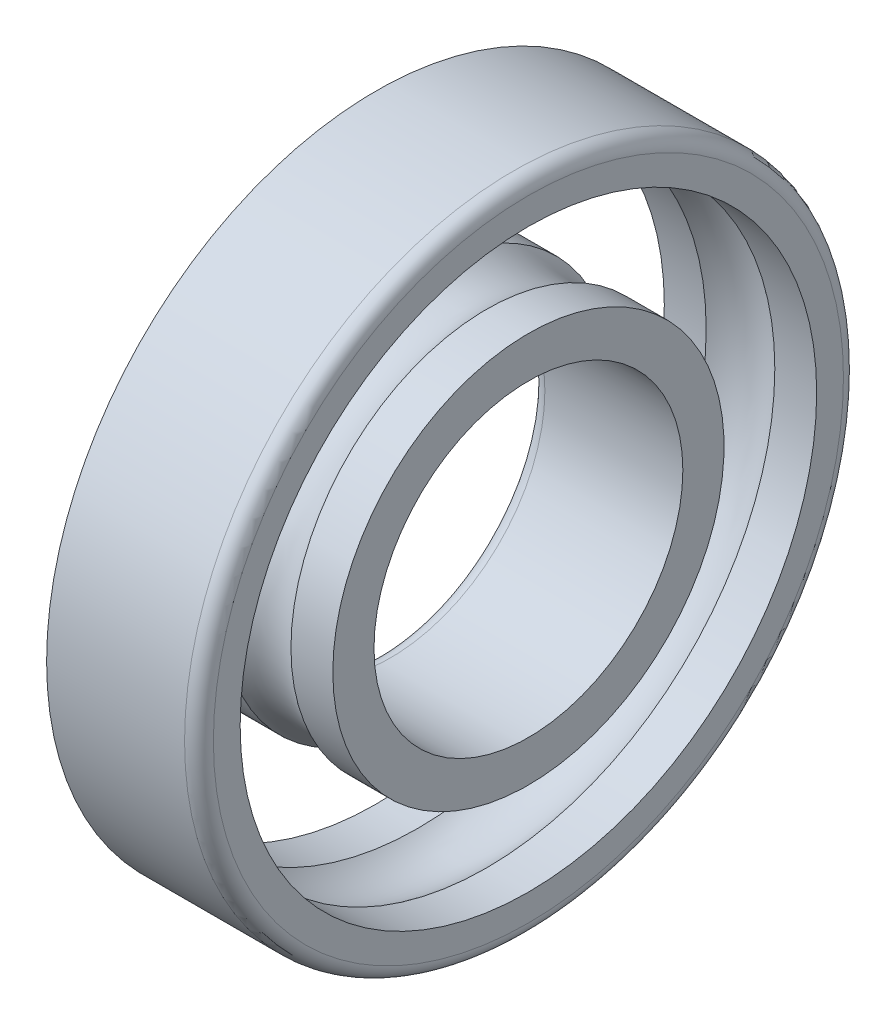
SolidWorks part; units mm, degrees
material "合金钢"
ref_plane "前视基准面" through (0, 0, 0) normal (0, 0, 1) x (1, 0, 0)
ref_plane "上视基准面" through (0, 0, 0) normal (0, 1, 0) x (1, 0, 0)
ref_plane "右视基准面" through (0, 0, 0) normal (1, 0, 0) x (0, 0, -1)
sketch "草图1" plane through (0, 0, 0) normal (0, 0, 1) x (1, 0, 0)
  line L0 (-49.6593, 0) -> (79.1925, 0) construction
  line L1 (8.3329, 70) -> (18.5, 70)
  line L2 (-18.5, 80) -> (18.5, 80)
  line L3 (-18.5, 80) -> (-18.5, 70)
  line L4 (-18.5, 70) -> (-8.3329, 70)
  line L5 (18.5, 80) -> (18.5, 70)
  line L6 (-18.5, 47.5) -> (-8.3329, 47.5)
  line L7 (-18.5, 47.5) -> (-18.5, 37.5)
  line L8 (-18.5, 37.5) -> (18.5, 37.5)
  line L9 (18.5, 47.5) -> (18.5, 37.5)
  line L10 (8.3329, 47.5) -> (18.5, 47.5)
  arc A0 (8.3329, 70) -> (-8.3329, 70) centre (0, 58.75) ccw
  arc A1 (-8.3329, 47.5) -> (8.3329, 47.5) centre (0, 58.75) ccw
  dimension "D5" = 14
  dimension "D1" = 70
  dimension "D2" = 18.5
  dimension "D3" = 18.5
  dimension "D4" = 80
  dimension "D6" = 21.25
  dimension "D7" = 37.5
  dimension "D8" = 47.5
  dimension "D9" = 18.5
  dimension "D10" = 18.5
  dimension "D11" = 58.75
revolve "旋转1" add sketch "草图1" angle 360 about L0
fillet "圆角1" radius 3.5 1 edges at (18.5, 0, 80)
fillet "圆角2" radius 3.5 1 edges at (-18.5, 0, 37.5)
